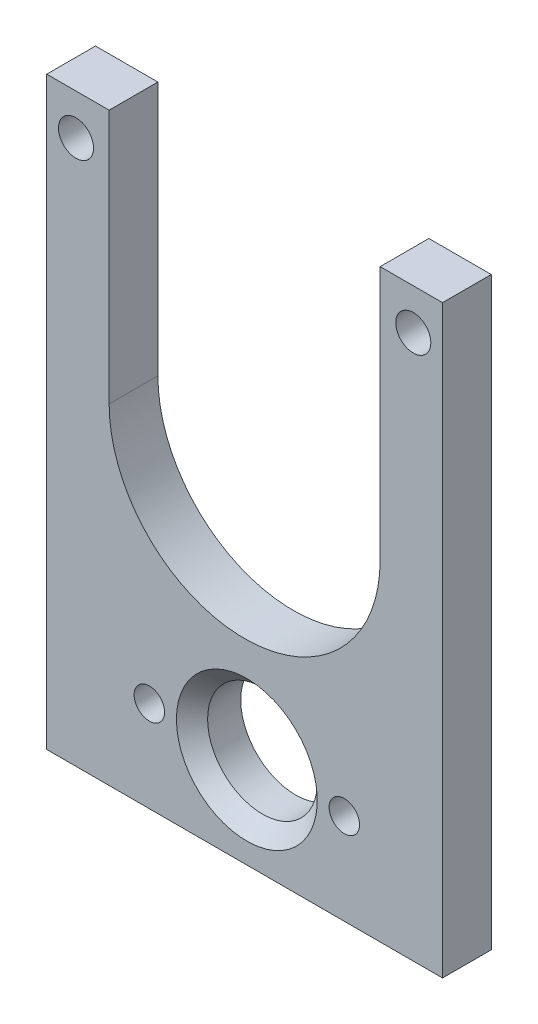
SolidWorks part; units mm, degrees
ref_plane "Plan de face" through (0, 0, 0) normal (0, 0, 1) x (1, 0, 0)
ref_plane "Plan de dessus" through (0, 0, 0) normal (0, 1, 0) x (1, 0, 0)
ref_plane "Plan de droite" through (0, 0, 0) normal (1, 0, 0) x (0, 0, -1)
sketch "Esquisse1" plane through (0, 0, 0) normal (0, 0, 1) x (1, 0, 0)
  line L0 (-26.0696, 64.3276) -> (-17.9416, 64.3276)
  line L1 (-17.9416, 64.3276) -> (-17.9416, 13.5276)
  line L2 (-17.9416, 13.5276) -> (17.3644, 13.5276)
  line L3 (17.3644, 13.5276) -> (17.3644, 64.3276)
  line L4 (17.3644, 64.3276) -> (25.4924, 64.3276)
  line L5 (25.4924, 64.3276) -> (25.4924, -11.8724)
  line L6 (25.4924, -11.8724) -> (-26.0696, -11.8724)
  line L7 (-26.0696, 64.3276) -> (-26.0696, -11.8724)
  circle A0 centre (0, 0) radius 7.1438
  circle A1 centre (21.6824, 59.0249) radius 2.286
  circle A2 centre (-22.2596, 59.0249) radius 2.286
  dimension "D1" = 14.2875
  dimension "D8" = 4.572
  dimension "D9" = 4.572
  dimension "D11" = 5.3026
  dimension "D2" = 59.0249
  dimension "D3" = 8.128
  dimension "D4" = 76.2
  dimension "D5" = 25.4
  dimension "D6" = 3.81
  dimension "D7" = 3.81
  dimension "D10" = 43.942
  dimension "D12" = 5.3026
  dimension "D13" = 26.0696
extrude "Boss.-Extru.1" add sketch "Esquisse1" along normal blind 6.35
sketch "Esquisse3" plane through (0, 0, 6.35) normal (0, 0, 1) x (1, 0, 0)
  circle A0 centre (12.7, 0) radius 1.9844
  dimension "D1" = 3.9688
  dimension "D2" = 12.7
extrude "Enlèv. mat.-Extru.1" cut sketch "Esquisse3" against normal through all
mirror "Symétrie1" about plane through (0, 0, 0) normal (1, 0, 0) of "Enlèv. mat.-Extru.1"
sketch "Sketch1" plane through (0, 0, 6.35) normal (0, 0, 1) x (1, 0, 0)
  line L1 (17.3644, 13.5276) -> (-17.9416, 13.5276) construction
  line L3 (-17.9416, 13.5276) -> (-17.9416, 64.3276) construction
  line L6 (17.3644, 64.3276) -> (17.3644, 13.5276) construction
  line L7 (-17.9416, 31.1806) -> (-17.9416, 13.5276)
  line L8 (-17.9416, 13.5276) -> (17.3644, 13.5276)
  line L9 (17.3644, 13.5276) -> (17.3644, 31.1806)
  arc A0 (-17.9416, 31.1806) -> (17.3644, 31.1806) centre (-0.2886, 31.1806) ccw
  line M10 (17.3644, 64.3276) -> (17.3644, 13.5276)
  line M11 (17.3644, 13.5276) -> (-17.9416, 13.5276)
  line M12 (-17.9416, 13.5276) -> (-17.9416, 64.3276)
extrude "Boss-Extrude1" add sketch "Sketch1" against normal up to surface (6.35 mm away) contours A0 L8 M12 | A0 M11 M10 up to face at (-14.6844, 0, 0)
chamfer "Chamfer1" distance 2.032 angle 45 1 edges at (7.1438, 0, 6.35)
